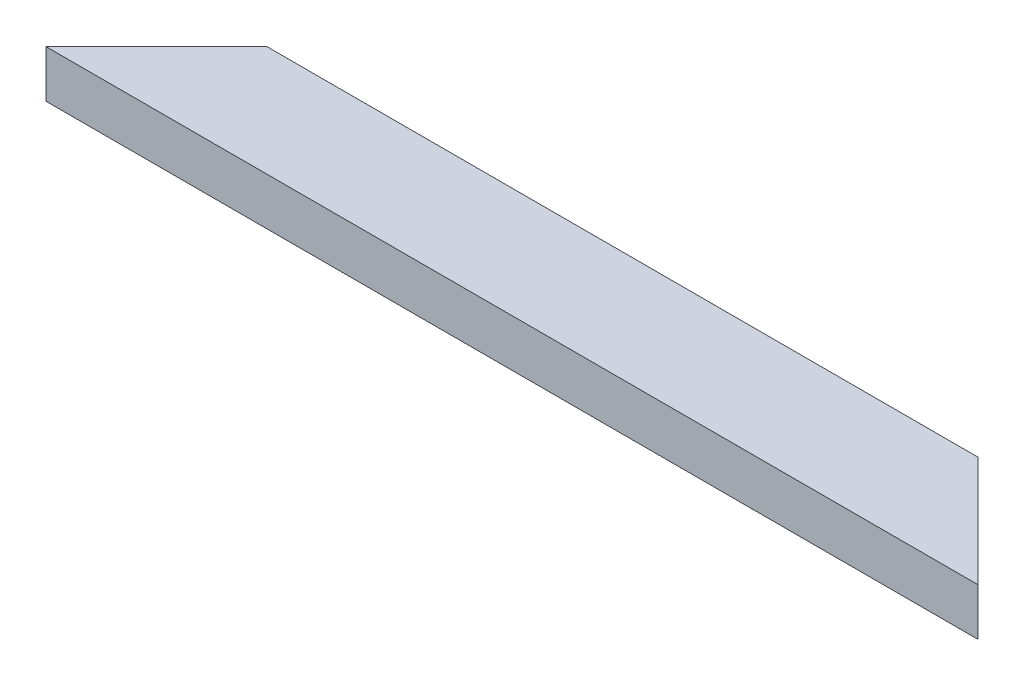
SolidWorks part; units mm, degrees
material "Pine"
ref_plane "Front Plane" through (0, 0, 0) normal (0, 0, 1) x (1, 0, 0)
ref_plane "Top Plane" through (0, 0, 0) normal (0, 1, 0) x (1, 0, 0)
ref_plane "Right Plane" through (0, 0, 0) normal (1, 0, 0) x (0, 0, -1)
sketch "Sketch1" plane through (0, 0, 0) normal (0, 1, 0) x (1, 0, 0)
  line L0 (0, 0) -> (750, 0)
  line L1 (750, 0) -> (661.1, 88.9)
  line L2 (661.1, 88.9) -> (88.9, 88.9)
  line L3 (88.9, 88.9) -> (0, 0)
  line L4 (375, 0) -> (375, 88.9) construction
  line L5 (0, 0) -> (375, 375) construction
  line L6 (375, 375) -> (750, 0) construction
  point P3 (355.8539, 440.0415)
  dimension "D1" = 88.9
  dimension "D2" = 750
extrude "Boss-Extrude1" add sketch "Sketch1" along normal blind 38.1
